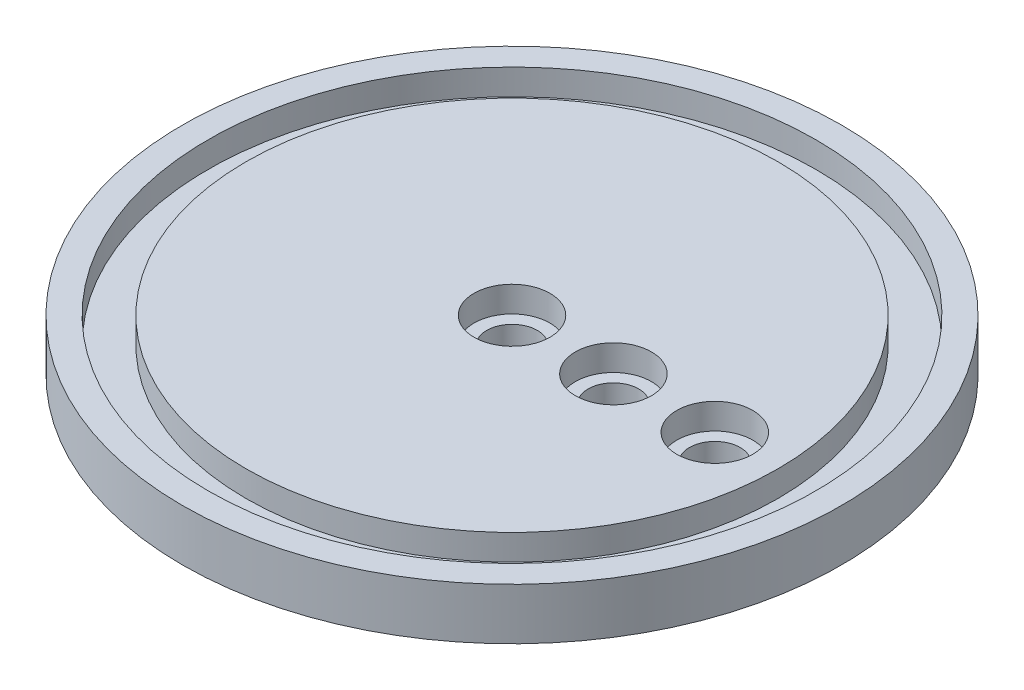
SolidWorks part; units mm, degrees
material "ABS"
ref_plane "Front Plane" through (0, 0, 0) normal (0, 0, 1) x (1, 0, 0)
ref_plane "Top Plane" through (0, 0, 0) normal (0, 1, 0) x (1, 0, 0)
ref_plane "Right Plane" through (0, 0, 0) normal (1, 0, 0) x (0, 0, -1)
sketch "Sketch2" plane through (0, 0, 0) normal (0, 1, 0) x (1, 0, 0)
  circle A0 centre (0, 0) radius 1
  circle A1 centre (4, 0) radius 1
  circle A2 centre (8, 0) radius 1
  circle A4 centre (0, 0) radius 13
  circle A6 centre (0, 0) radius 9 construction
  circle A7 centre (0, 0) radius 11 construction
  point P19 (0, 0)
  dimension "D1" = 2
  dimension "D3" = 2
  dimension "D4" = 2
  dimension "D5" = 4
  dimension "D8" = 26
  dimension "D2" = 3
extrude "Boss-Extrude2" add sketch "Sketch2" along normal blind 1.016
sketch "Sketch3" plane through (0, 1.016, 0) normal (0, 1, 0) x (1, 0, 0)
  circle A0 centre (0, 0) radius 1.5
  circle A1 centre (0, 0) radius 1 construction
  circle A2 centre (4, 0) radius 1.5
  circle A3 centre (8, 0) radius 1.5
  circle A4 centre (0, 0) radius 13
  circle A8 centre (0, 0) radius 10.492
  circle A9 centre (0, 0) radius 11.992
  circle M6 centre (0, 0) radius 13
  dimension "D1" = 0.5
  dimension "D2" = 1.5
extrude "Boss-Extrude4" add sketch "Sketch3" along normal blind 1.016 contours A9 M6 | A8 A0 A2 A3
